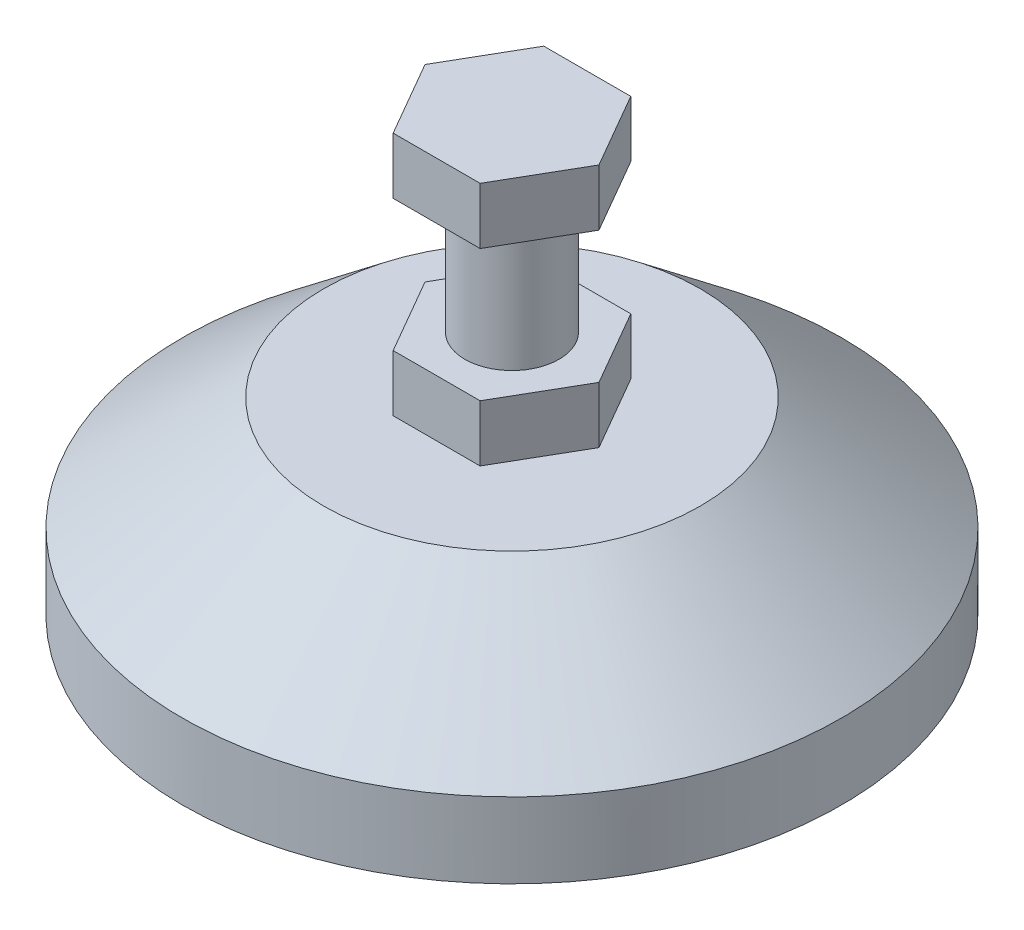
SolidWorks part; units mm, degrees
material "Сталь 3 ГОСТ 535-88"
ref_plane "Спереди" through (0, 0, 0) normal (0, 0, 1) x (1, 0, 0)
ref_plane "Сверху" through (0, 0, 0) normal (0, 1, 0) x (1, 0, 0)
ref_plane "Справа" through (0, 0, 0) normal (1, 0, 0) x (0, 0, -1)
sketch "Эскиз1" plane through (0, 0, 0) normal (0, 1, 0) x (1, 0, 0)
  circle A0 centre (0, 0) radius 35
  dimension "D1" = 70
extrude "Бобышка-Вытянуть1" add sketch "Эскиз1" along normal blind 8
sketch "Эскиз2" plane through (0, 8, 0) normal (0, 1, 0) x (1, 0, 0)
  circle A1 centre (0, 0) radius 35
  circle A2 centre (0, 0) radius 35
  dimension "D1" = 0
ref_plane "Плоскость1" through (0, 20, 0) normal (0, 1, 0) x (1, 0, 0)
sketch "Эскиз3" plane through (0, 20, 0) normal (0, 1, 0) x (1, 0, 0)
  circle A0 centre (0, 0) radius 20
  dimension "D1" = 40
loft "По сечениям1" add profiles "Эскиз2", "Эскиз3"
sketch "Эскиз4" plane through (0, 20, 0) normal (0, 1, 0) x (1, 0, 0)
  line L1 (9.2376, 0) -> (4.6188, 8)
  line L2 (4.6188, 8) -> (-4.6188, 8)
  line L3 (-4.6188, 8) -> (-9.2376, 0)
  line L4 (-9.2376, 0) -> (-4.6188, -8)
  line L5 (-4.6188, -8) -> (4.6188, -8)
  line L6 (4.6188, -8) -> (9.2376, 0)
  circle A0 centre (0, 0) radius 8 construction
  dimension "D1" = 16
extrude "Бобышка-Вытянуть2" add sketch "Эскиз4" along normal blind 6 separate body
sketch "Эскиз5" plane through (0, 26, 0) normal (0, 1, 0) x (1, 0, 0)
  circle A0 centre (0, 0) radius 5
  dimension "D1" = 10
extrude "Бобышка-Вытянуть3" add sketch "Эскиз5" along normal blind 70 separate body
cosmetic thread "Условное изображение резьбы1" parameters "D2"=8.344
chamfer "Фаска1" distance 1 angle 45 1 edges at (0, 96, 5)
move or copy body "Тело-Переместить/Копировать1" bodies to move or copy 105 copy yes number of copies 1 translate (0, 20, 0)
sketch "Эскиз6" plane through (0, 0, 0) normal (0, 0, 1) x (1, 0, 0)
  line L0 (-4.6188, 26) -> (4.6188, 26) construction
  line L1 (-32.8149, 107.0137) -> (38.3328, 107.0137)
  line L2 (-32.8149, 107.0137) -> (-32.8149, 43)
  line L3 (-32.8149, 43) -> (38.3328, 43)
  line L4 (38.3328, 107.0137) -> (38.3328, 43)
  dimension "D1" = 17
extrude "Вырез-Вытянуть1" cut sketch "Эскиз6" against normal blind 70 and the other way blind 70
